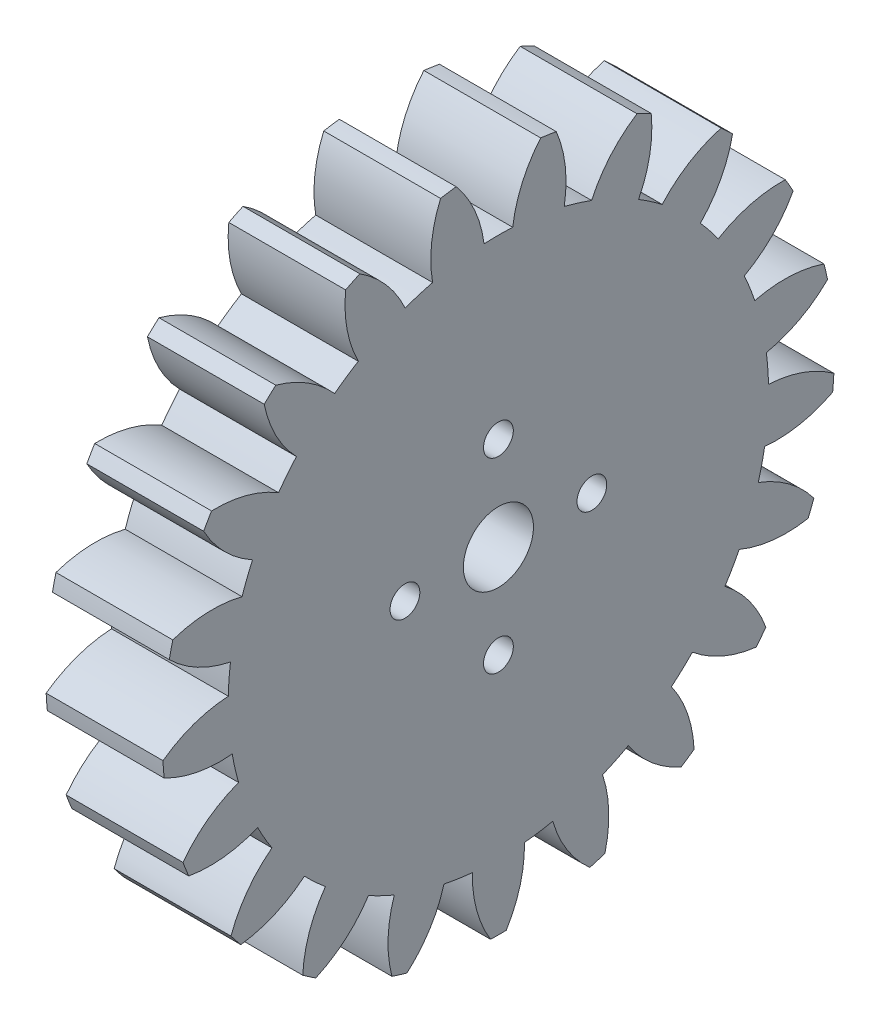
SolidWorks part; units mm, degrees
ref_plane "Plane1" through (0, 0, 0) normal (0, 0, 1) x (1, 0, 0)
ref_plane "Plane2" through (0, 0, 0) normal (0, 1, 0) x (1, 0, 0)
ref_plane "Plane3" through (0, 0, 0) normal (1, 0, 0) x (0, 0, -1)
sketch "HoldingSke" plane through (0, 0, 0) normal (0, 1, 0) x (1, 0, 0)
  line L0 (0, 0) -> (0.3734, -0.1433)
  line L1 (-15, 0) -> (100, 0) construction
  line L2 (0, 0) -> (-2.1039, 2.3779)
  line L3 (0, 0) -> (-11.863, 4.5341)
  line L4 (0, 0) -> (8.0624, 3.0949)
  line L5 (0, 0) -> (-9.3695, -3.4946)
  line L6 (0, 0) -> (-12.4344, -8.3896)
  line L7 (-2.1039, 2.3779) -> (1.1249, 17.0263)
  line L8 (-76.2, 54.61) -> (-75.2, 54.61)
  line L9 (-71.009, 38.7566) -> (-53.1078, 45.2721)
  line L10 (-76.2, 71.12) -> (104.1128, 71.12)
  line L11 (0, 0) -> (-15, 0)
  line L12 (-76.2, 101.6) -> (-76.113, 101.6)
  line L13 (24.9733, 27.94) -> (52.9518, 28.4284)
  line L14 (24.9733, 27.94) -> (24.9743, 27.94)
  line L15 (24.9733, 27.94) -> (100.4006, 29.5858)
  line L16 (-63.627, -2.5) -> (-12.827, -2.5)
  circle A0 centre (0, 0) radius 3
  circle A1 centre (0, 0) radius 12
  circle A2 centre (0, 0) radius 12
  circle A3 centre (0, 0) radius 3
  dimension "MHD" = 24
  dimension "Hub_dia" = 24
  dimension "Bore" = 6
  dimension "MBD" = 6
  dimension "Num_teeth" = 21
  dimension "Pitch" = 0.4
  dimension "Overall_len" = 10
  dimension "Show_teeth" = 21
  dimension "Thickness" = 15
  dimension "OAL" = 15.0001
  dimension "T_dim" = 1
  dimension "Ap" = 20
  dimension "H" = 19.05
  dimension "Pitch_radius" = 180.3128
  dimension "Width" = 15
  dimension "Backlash" = 0.087
  dimension "Addendum_fac" = 1
  dimension "Dedendum_fac" = 1.25
  dimension "Clearance_fac" = 0.25
  dimension "Dedendum_add" = 0.001
  dimension "Module" = 2.5
sketch "BasProSke" plane through (0, 0, 0) normal (0, 1, 0) x (1, 0, 0)
  line L0 (-10, 0) -> (60, 0) construction
  line L1 (0, 0) -> (0, 28.75)
  line L2 (0, 0) -> (15, 0)
  line L3 (15, 0) -> (15, 28.75)
  line L4 (15, 28.75) -> (0, 28.75)
  dimension "Thickness" = 15
  dimension "Diameter" = 57.5
revolve "Base-Revolve" add sketch "BasProSke" angle 360 about L0
sketch "TooCutSke" plane through (0, 0, 0) normal (1, 0, 0) x (0, 0, -1)
  line L1 (0, 0) -> (0, 107) construction
  line L2 (0, 0) -> (-2.1138, 26.1648) construction
  line L3 (0, 0) -> (-7.8061, 51.7901) construction
  line L4 (-2.1138, 26.1648) -> (-3.9031, 25.8951) construction
  arc A0 (1.226, 23.0915) -> (-1.226, 23.0915) centre (0, 0) ccw
  arc A1 (3.6363, 28.5447) -> (-3.6363, 28.5447) centre (0, 0) ccw
  circle A2 centre (0, 0) radius 26.25 construction
  circle A3 centre (0, 0) radius 24.6669 construction
  arc A4 (-1.226, 23.0915) -> (-3.6363, 28.5447) centre (-11.6397, 21.748) ccw
  arc A5 (3.6363, 28.5447) -> (1.226, 23.0915) centre (11.6397, 21.748) ccw
  dimension "Root_dia" = 46.248
  dimension "Overcut_dia" = 57.5508
  dimension "Pitch_dia" = 52.5
  dimension "Base_dia" = 49.3339
  dimension "Flank_rad" = 10.5
  dimension "Half_ang" = 8.571
  dimension "Half_CT" = 1.8094
extrude "ToothCut" cut sketch "TooCutSke" along normal through all
fillet "Breaks" [suppressed] radius 0.05
fillet "RootFillets" [suppressed] radius 0.626
pattern_circular "TeethCuts" count 21 every 17.143 about axis through (-10, 0, 0) along (1, 0, 0) of "ToothCut", "RootFillets", "Breaks"
sketch "HubNeaOneSke" plane through (0, 0, 0) normal (-1, 0, 0) x (0, 0, 1)
  circle A0 centre (0, 0) radius 12
  dimension "Diameter" = 24
extrude "HubNearOne" add sketch "HubNeaOneSke" along normal blind 35.0001
sketch "HubNeaBotSke" plane through (0, 0, 0) normal (-1, 0, 0) x (0, 0, 1)
  circle A0 centre (0, 0) radius 12
  dimension "Diameter" = 24
extrude "HubNearBoth" [suppressed] add sketch "HubNeaBotSke" along normal blind 17.5
ref_plane "FarPln" through (15, 0, 0) normal (1, 0, 0) x (0, 0, -1)
sketch "HubFarSke" plane through (15, 0, 0) normal (1, 0, 0) x (0, 0, -1)
  circle A0 centre (0, 0) radius 12
  dimension "Diameter" = 24
extrude "HubFar" [suppressed] add sketch "HubFarSke" along normal blind 17.5
sketch "BorSke" plane through (0, 0, 0) normal (1, 0, 0) x (0, 0, -1)
  circle A0 centre (0, 0) radius 3
  dimension "Diameter" = 6
extrude "Bore" cut sketch "BorSke" along normal mid plane 30.0001
sketch "KeySke" plane through (0, 0, 0) normal (1, 0, 0) x (0, 0, -1)
  line L0 (-1, 0) -> (-1, 4)
  line L1 (-1, 4) -> (1, 4)
  line L2 (1, 4) -> (1, 0)
  line L3 (0, 0) -> (0, 34) construction
  line L4 (-1, 0) -> (1, 0)
  dimension "Offset" = 4
  dimension "Width" = 2
extrude "Keyway" [suppressed] cut sketch "KeySke" along normal mid plane 30.0001
pattern_circular "Keyway2" [suppressed] count 2 every 90 about axis through (-10, 0, 0) along (1, 0, 0)
sketch "草圖1" plane through (0, 0, 0) normal (0, 1, 0) x (1, 0, 0)
  line L1 (-35.0001, -11.863) -> (-35.0001, -15.4488)
  line L2 (-35.0001, 12) -> (0, 12)
  line L3 (-35.0001, 12) -> (-35.0001, -11.863)
  line L5 (0, 12) -> (0, -11.863)
  line L6 (-35.0001, -15.4488) -> (0, -15.4488)
  line L7 (0, -15.4488) -> (0, -11.863)
extrude "除料-伸長1" cut sketch "草圖1" against normal through all both and the other way through all
sketch "草圖2" plane through (0, 0, 0) normal (-1, 0, 0) x (0, 0, 1)
  line L0 (0, 0) -> (0, 11.4291) construction
  line L1 (0, 0) -> (11.4291, 0) construction
  line L2 (0, 0) -> (0, -11.4291) construction
  line L3 (0, 0) -> (-11.4291, 0) construction
  circle A0 centre (0, 8) radius 1.275
  circle A1 centre (8, 0) radius 1.275
  circle A2 centre (0, -8) radius 1.275
  circle A3 centre (-8, 0) radius 1.275
  point P17 (0, 0)
  dimension "D1" = 8
  dimension "D2" = 2.55
  dimension "D3" = 4
extrude "除料-伸長2" cut sketch "草圖2" against normal through all
sketch "草圖3" plane through (0, 0, 0) normal (-1, 0, 0) x (0, 0, 1)
  arc A84 (15.6336, -24.1278) -> (16.7484, -23.3678) centre (0, 0) ccw
  arc A85 (16.7484, -23.3678) -> (14.8075, -17.7612) centre (6.2599, -23.8594) ccw
  arc A86 (14.8075, -17.7612) -> (16.6049, -16.0933) centre (0, 0) ccw
  arc A87 (16.6049, -16.0933) -> (22.0509, -18.4478) centre (23.3249, -8.0254) ccw
  arc A88 (22.0509, -18.4478) -> (22.8921, -17.393) centre (0, 0) ccw
  arc A89 (22.8921, -17.393) -> (19.3848, -12.6075) centre (13.0144, -20.9543) ccw
  arc A90 (19.3848, -12.6075) -> (20.6108, -10.484) centre (0, 0) ccw
  arc A91 (20.6108, -10.484) -> (26.5088, -11.1286) centre (24.6542, -0.7937) ccw
  arc A92 (26.5088, -11.1286) -> (27.0017, -9.8727) centre (0, 0) ccw
  arc A93 (27.0017, -9.8727) -> (22.2397, -6.3336) centre (18.6126, -16.1873) ccw
  arc A94 (22.2397, -6.3336) -> (22.7853, -3.9431) centre (0, 0) ccw
  arc A95 (22.7853, -3.9431) -> (28.6113, -2.8206) centre (23.7928, 6.5085) ccw
  arc A96 (28.6113, -2.8206) -> (28.7121, -1.4752) centre (0, 0) ccw
  arc A97 (28.7121, -1.4752) -> (23.1185, 0.503) centre (22.557, -9.9819) ccw
  arc A98 (23.1185, 0.503) -> (22.9353, 2.9482) centre (0, 0) ccw
  arc A99 (22.9353, 2.9482) -> (28.1716, 5.7381) centre (20.8173, 13.2324) ccw
  arc A100 (28.1716, 5.7381) -> (27.8714, 7.0534) centre (0, 0) ccw
  arc A101 (27.8714, 7.0534) -> (21.9432, 7.295) centre (24.4971, -2.8897) ccw
  arc A102 (21.9432, 7.295) -> (21.0473, 9.5775) centre (0, 0) ccw
  arc A103 (21.0473, 9.5775) -> (25.2287, 13.7868) centre (15.9922, 18.7805) ccw
  arc A104 (25.2287, 13.7868) -> (24.5541, 14.9552) centre (0, 0) ccw
  arc A105 (24.5541, 14.9552) -> (18.8181, 13.4388) centre (24.2605, 4.4593) ccw
  arc A106 (18.8181, 13.4388) -> (17.2892, 15.3558) centre (0, 0) ccw
  arc A107 (17.2892, 15.3558) -> (20.0441, 20.6106) centre (9.746, 22.6599) ccw
  arc A108 (20.0441, 20.6106) -> (19.0551, 21.5283) centre (0, 0) ccw
  arc A109 (19.0551, 21.5283) -> (14.0209, 18.3884) centre (21.8683, 11.4121) ccw
  arc A110 (14.0209, 18.3884) -> (11.9949, 19.7697) centre (0, 0) ccw
  arc A111 (11.9949, 19.7697) -> (13.0785, 25.603) centre (2.6339, 24.5259) ccw
  arc A112 (13.0785, 25.603) -> (11.863, 26.1884) centre (0, 0) ccw
  arc A113 (11.863, 26.1884) -> (7.9779, 21.7042) centre (17.5329, 17.3509) ccw
  arc A114 (7.9779, 21.7042) -> (5.6348, 22.427) centre (0, 0) ccw
  arc A115 (5.6348, 22.427) -> (4.9508, 28.3205) centre (-4.7123, 24.2126) ccw
  arc A116 (4.9508, 28.3205) -> (3.6167, 28.5216) centre (0, 0) ccw
  arc A117 (3.6167, 28.5216) -> (1.226, 23.0915) centre (11.6397, 21.748) ccw
  arc A118 (1.226, 23.0915) -> (-1.226, 23.0915) centre (0, 0) ccw
  arc A119 (-1.226, 23.0915) -> (-3.6167, 28.5216) centre (-11.6397, 21.748) ccw
  arc A120 (-3.6167, 28.5216) -> (-4.9508, 28.3205) centre (0, 0) ccw
  arc A121 (-4.9508, 28.3205) -> (-5.6348, 22.427) centre (4.7123, 24.2126) ccw
  arc A122 (-5.6348, 22.427) -> (-7.9779, 21.7042) centre (0, 0) ccw
  arc A123 (-7.9779, 21.7042) -> (-11.863, 26.1884) centre (-17.5329, 17.3509) ccw
  arc A124 (-11.863, 26.1884) -> (-13.0785, 25.603) centre (0, 0) ccw
  arc A125 (-13.0785, 25.603) -> (-11.9949, 19.7697) centre (-2.6339, 24.5259) ccw
  arc A126 (-11.9949, 19.7697) -> (-14.0209, 18.3884) centre (0, 0) ccw
  arc A127 (-14.0209, 18.3884) -> (-19.0551, 21.5283) centre (-21.8683, 11.4121) ccw
  arc A128 (-19.0551, 21.5283) -> (-20.0441, 20.6106) centre (0, 0) ccw
  arc A129 (-20.0441, 20.6106) -> (-17.2892, 15.3558) centre (-9.746, 22.6599) ccw
  arc A130 (-17.2892, 15.3558) -> (-18.8181, 13.4388) centre (0, 0) ccw
  arc A131 (-18.8181, 13.4388) -> (-24.5541, 14.9552) centre (-24.2605, 4.4593) ccw
  arc A132 (-24.5541, 14.9552) -> (-25.2287, 13.7868) centre (0, 0) ccw
  arc A133 (-25.2287, 13.7868) -> (-21.0473, 9.5775) centre (-15.9922, 18.7805) ccw
  arc A134 (-21.0473, 9.5775) -> (-21.9432, 7.295) centre (0, 0) ccw
  arc A135 (-21.9432, 7.295) -> (-27.8714, 7.0534) centre (-24.4971, -2.8897) ccw
  arc A136 (-27.8714, 7.0534) -> (-28.1716, 5.7381) centre (0, 0) ccw
  arc A137 (-28.1716, 5.7381) -> (-22.9353, 2.9482) centre (-20.8173, 13.2324) ccw
  arc A138 (-22.9353, 2.9482) -> (-23.1185, 0.503) centre (0, 0) ccw
  arc A139 (-23.1185, 0.503) -> (-28.7121, -1.4752) centre (-22.557, -9.9819) ccw
  arc A140 (-28.7121, -1.4752) -> (-28.6113, -2.8206) centre (0, 0) ccw
  arc A141 (-28.6113, -2.8206) -> (-22.7853, -3.9431) centre (-23.7928, 6.5085) ccw
  arc A142 (-22.7853, -3.9431) -> (-22.2397, -6.3336) centre (0, 0) ccw
  arc A143 (-22.2397, -6.3336) -> (-27.0017, -9.8727) centre (-18.6126, -16.1873) ccw
  arc A144 (-27.0017, -9.8727) -> (-26.5088, -11.1286) centre (0, 0) ccw
  arc A145 (-26.5088, -11.1286) -> (-20.6108, -10.484) centre (-24.6542, -0.7937) ccw
  arc A146 (-20.6108, -10.484) -> (-19.3848, -12.6075) centre (0, 0) ccw
  arc A147 (-19.3848, -12.6075) -> (-22.8921, -17.393) centre (-13.0144, -20.9543) ccw
  arc A148 (-22.8921, -17.393) -> (-22.0509, -18.4478) centre (0, 0) ccw
  arc A149 (-22.0509, -18.4478) -> (-16.6049, -16.0933) centre (-23.3249, -8.0254) ccw
  arc A150 (-16.6049, -16.0933) -> (-14.8075, -17.7612) centre (0, 0) ccw
  arc A151 (-14.8075, -17.7612) -> (-16.7484, -23.3678) centre (-6.2599, -23.8594) ccw
  arc A152 (-16.7484, -23.3678) -> (-15.6336, -24.1278) centre (0, 0) ccw
  arc A153 (-15.6336, -24.1278) -> (-11.1236, -20.2728) centre (-19.9231, -14.544) ccw
  arc A154 (-11.1236, -20.2728) -> (-8.9144, -21.3367) centre (0, 0) ccw
  arc A155 (-8.9144, -21.3367) -> (-9.1165, -27.2663) centre (1.0509, -24.6445) ccw
  arc A156 (-9.1165, -27.2663) -> (-7.8273, -27.664) centre (0, 0) ccw
  arc A157 (-7.8273, -27.664) -> (-4.6539, -22.6508) centre (-14.7511, -19.7703) ccw
  arc A158 (-4.6539, -22.6508) -> (-2.2293, -23.0163) centre (0, 0) ccw
  arc A159 (-2.2293, -23.0163) -> (-0.6746, -28.7421) centre (8.2683, -23.2399) ccw
  arc A160 (-0.6746, -28.7421) -> (0.6746, -28.7421) centre (0, 0) ccw
  arc A161 (0.6746, -28.7421) -> (2.2293, -23.0163) centre (-8.2683, -23.2399) ccw
  arc A162 (2.2293, -23.0163) -> (4.6539, -22.6508) centre (0, 0) ccw
  arc A163 (4.6539, -22.6508) -> (7.8273, -27.664) centre (14.7511, -19.7703) ccw
  arc A164 (7.8273, -27.664) -> (9.1165, -27.2663) centre (0, 0) ccw
  arc A165 (9.1165, -27.2663) -> (8.9144, -21.3367) centre (-1.0509, -24.6445) ccw
  arc A166 (8.9144, -21.3367) -> (11.1236, -20.2728) centre (0, 0) ccw
  arc A167 (11.1236, -20.2728) -> (15.6336, -24.1278) centre (19.9231, -14.544) ccw
  arc A168 (15.6336, -24.1278) -> (16.7484, -23.3678) centre (0, 0) ccw
  arc A169 (16.7484, -23.3678) -> (14.8075, -17.7612) centre (6.2599, -23.8594) ccw
  arc A170 (14.8075, -17.7612) -> (16.6049, -16.0933) centre (0, 0) ccw
  arc A171 (16.6049, -16.0933) -> (22.0509, -18.4478) centre (23.3249, -8.0254) ccw
  arc A172 (22.0509, -18.4478) -> (22.8921, -17.393) centre (0, 0) ccw
  arc A173 (22.8921, -17.393) -> (19.3848, -12.6075) centre (13.0144, -20.9543) ccw
  arc A174 (19.3848, -12.6075) -> (20.6108, -10.484) centre (0, 0) ccw
  arc A175 (20.6108, -10.484) -> (26.5088, -11.1286) centre (24.6542, -0.7937) ccw
  arc A176 (26.5088, -11.1286) -> (27.0017, -9.8727) centre (0, 0) ccw
  arc A177 (27.0017, -9.8727) -> (22.2397, -6.3336) centre (18.6126, -16.1873) ccw
  arc A178 (22.2397, -6.3336) -> (22.7853, -3.9431) centre (0, 0) ccw
  arc A179 (22.7853, -3.9431) -> (28.6113, -2.8206) centre (23.7928, 6.5085) ccw
  arc A180 (28.6113, -2.8206) -> (28.7121, -1.4752) centre (0, 0) ccw
  arc A181 (28.7121, -1.4752) -> (23.1185, 0.503) centre (22.557, -9.9819) ccw
  arc A182 (23.1185, 0.503) -> (22.9353, 2.9482) centre (0, 0) ccw
  arc A183 (22.9353, 2.9482) -> (28.1716, 5.7381) centre (20.8173, 13.2324) ccw
  arc A184 (28.1716, 5.7381) -> (27.8714, 7.0534) centre (0, 0) ccw
  arc A185 (27.8714, 7.0534) -> (21.9432, 7.295) centre (24.4971, -2.8897) ccw
  arc A186 (21.9432, 7.295) -> (21.0473, 9.5775) centre (0, 0) ccw
  arc A187 (21.0473, 9.5775) -> (25.2287, 13.7868) centre (15.9922, 18.7805) ccw
  arc A188 (25.2287, 13.7868) -> (24.5541, 14.9552) centre (0, 0) ccw
  arc A189 (24.5541, 14.9552) -> (18.8181, 13.4388) centre (24.2605, 4.4593) ccw
  arc A190 (18.8181, 13.4388) -> (17.2892, 15.3558) centre (0, 0) ccw
  arc A191 (17.2892, 15.3558) -> (20.0441, 20.6106) centre (9.746, 22.6599) ccw
  arc A192 (20.0441, 20.6106) -> (19.0551, 21.5283) centre (0, 0) ccw
  arc A193 (19.0551, 21.5283) -> (14.0209, 18.3884) centre (21.8683, 11.4121) ccw
  arc A194 (14.0209, 18.3884) -> (11.9949, 19.7697) centre (0, 0) ccw
  arc A195 (11.9949, 19.7697) -> (13.0785, 25.603) centre (2.6339, 24.5259) ccw
  arc A196 (13.0785, 25.603) -> (11.863, 26.1884) centre (0, 0) ccw
  arc A197 (11.863, 26.1884) -> (7.9779, 21.7042) centre (17.5329, 17.3509) ccw
  arc A198 (7.9779, 21.7042) -> (5.6348, 22.427) centre (0, 0) ccw
  arc A199 (5.6348, 22.427) -> (4.9508, 28.3205) centre (-4.7123, 24.2126) ccw
  arc A200 (4.9508, 28.3205) -> (3.6167, 28.5216) centre (0, 0) ccw
  arc A201 (3.6167, 28.5216) -> (1.226, 23.0915) centre (11.6397, 21.748) ccw
  arc A202 (1.226, 23.0915) -> (-1.226, 23.0915) centre (0, 0) ccw
  arc A203 (-1.226, 23.0915) -> (-3.6167, 28.5216) centre (-11.6397, 21.748) ccw
  arc A204 (-3.6167, 28.5216) -> (-4.9508, 28.3205) centre (0, 0) ccw
  arc A205 (-4.9508, 28.3205) -> (-5.6348, 22.427) centre (4.7123, 24.2126) ccw
  arc A206 (-5.6348, 22.427) -> (-7.9779, 21.7042) centre (0, 0) ccw
  arc A207 (-7.9779, 21.7042) -> (-11.863, 26.1884) centre (-17.5329, 17.3509) ccw
  arc A208 (-11.863, 26.1884) -> (-13.0785, 25.603) centre (0, 0) ccw
  arc A209 (-13.0785, 25.603) -> (-11.9949, 19.7697) centre (-2.6339, 24.5259) ccw
  arc A210 (-11.9949, 19.7697) -> (-14.0209, 18.3884) centre (0, 0) ccw
  arc A211 (-14.0209, 18.3884) -> (-19.0551, 21.5283) centre (-21.8683, 11.4121) ccw
  arc A212 (-19.0551, 21.5283) -> (-20.0441, 20.6106) centre (0, 0) ccw
  arc A213 (-20.0441, 20.6106) -> (-17.2892, 15.3558) centre (-9.746, 22.6599) ccw
  arc A214 (-17.2892, 15.3558) -> (-18.8181, 13.4388) centre (0, 0) ccw
  arc A215 (-18.8181, 13.4388) -> (-24.5541, 14.9552) centre (-24.2605, 4.4593) ccw
  arc A216 (-24.5541, 14.9552) -> (-25.2287, 13.7868) centre (0, 0) ccw
  arc A217 (-25.2287, 13.7868) -> (-21.0473, 9.5775) centre (-15.9922, 18.7805) ccw
  arc A218 (-21.0473, 9.5775) -> (-21.9432, 7.295) centre (0, 0) ccw
  arc A219 (-21.9432, 7.295) -> (-27.8714, 7.0534) centre (-24.4971, -2.8897) ccw
  arc A220 (-27.8714, 7.0534) -> (-28.1716, 5.7381) centre (0, 0) ccw
  arc A221 (-28.1716, 5.7381) -> (-22.9353, 2.9482) centre (-20.8173, 13.2324) ccw
  arc A222 (-22.9353, 2.9482) -> (-23.1185, 0.503) centre (0, 0) ccw
  arc A223 (-23.1185, 0.503) -> (-28.7121, -1.4752) centre (-22.557, -9.9819) ccw
  arc A224 (-28.7121, -1.4752) -> (-28.6113, -2.8206) centre (0, 0) ccw
  arc A225 (-28.6113, -2.8206) -> (-22.7853, -3.9431) centre (-23.7928, 6.5085) ccw
  arc A226 (-22.7853, -3.9431) -> (-22.2397, -6.3336) centre (0, 0) ccw
  arc A227 (-22.2397, -6.3336) -> (-27.0017, -9.8727) centre (-18.6126, -16.1873) ccw
  arc A228 (-27.0017, -9.8727) -> (-26.5088, -11.1286) centre (0, 0) ccw
  arc A229 (-26.5088, -11.1286) -> (-20.6108, -10.484) centre (-24.6542, -0.7937) ccw
  arc A230 (-20.6108, -10.484) -> (-19.3848, -12.6075) centre (0, 0) ccw
  arc A231 (-19.3848, -12.6075) -> (-22.8921, -17.393) centre (-13.0144, -20.9543) ccw
  arc A232 (-22.8921, -17.393) -> (-22.0509, -18.4478) centre (0, 0) ccw
  arc A233 (-22.0509, -18.4478) -> (-16.6049, -16.0933) centre (-23.3249, -8.0254) ccw
  arc A234 (-16.6049, -16.0933) -> (-14.8075, -17.7612) centre (0, 0) ccw
  arc A235 (-14.8075, -17.7612) -> (-16.7484, -23.3678) centre (-6.2599, -23.8594) ccw
  arc A236 (-16.7484, -23.3678) -> (-15.6336, -24.1278) centre (0, 0) ccw
  arc A237 (-15.6336, -24.1278) -> (-11.1236, -20.2728) centre (-19.9231, -14.544) ccw
  arc A238 (-11.1236, -20.2728) -> (-8.9144, -21.3367) centre (0, 0) ccw
  arc A239 (-8.9144, -21.3367) -> (-9.1165, -27.2663) centre (1.0509, -24.6445) ccw
  arc A240 (-9.1165, -27.2663) -> (-7.8273, -27.664) centre (0, 0) ccw
  arc A241 (-7.8273, -27.664) -> (-4.6539, -22.6508) centre (-14.7511, -19.7703) ccw
  arc A242 (-4.6539, -22.6508) -> (-2.2293, -23.0163) centre (0, 0) ccw
  arc A243 (-2.2293, -23.0163) -> (-0.6746, -28.7421) centre (8.2683, -23.2399) ccw
  arc A244 (-0.6746, -28.7421) -> (0.6746, -28.7421) centre (0, 0) ccw
  arc A245 (0.6746, -28.7421) -> (2.2293, -23.0163) centre (-8.2683, -23.2399) ccw
  arc A246 (2.2293, -23.0163) -> (4.6539, -22.6508) centre (0, 0) ccw
  arc A247 (4.6539, -22.6508) -> (7.8273, -27.664) centre (14.7511, -19.7703) ccw
  arc A248 (7.8273, -27.664) -> (9.1165, -27.2663) centre (0, 0) ccw
  arc A249 (9.1165, -27.2663) -> (8.9144, -21.3367) centre (-1.0509, -24.6445) ccw
  arc A250 (8.9144, -21.3367) -> (11.1236, -20.2728) centre (0, 0) ccw
  arc A251 (11.1236, -20.2728) -> (15.6336, -24.1278) centre (19.9231, -14.544) ccw
  dimension "D1" = 0
extrude "除料-伸長3" cut sketch "草圖3" against normal blind 5
equation "' \"Module@HoldingSke\" = 6.35"
equation "' \"Num_teeth@HoldingSke\" = 12"
equation "' \"Ap@HoldingSke\" =  20"
equation "' \"Ap@HoldingSke\" = 20"
equation "' \"Width@HoldingSke\" = 0.5 * 25.4"
equation "' \"Hub_dia@HoldingSke\"= 1 * 25.4"
equation "' \"Hub_dia@HoldingSke\" = 1 * 25.4"
equation "' \"Overall_len@HoldingSke\" = 1.0 * 25.4"
equation "' \"Bore@HoldingSke\" = 0.75 * 25.4"
equation "' \"T_dim@HoldingSke\" = 0.1 * 25.4"
equation "' \"Width@KeySke\" = 0.25 * 25.4"
equation "' \"Show_teeth@HoldingSke\" = 13"
equation "' \"Backlash@HoldingSke\" = 0.009 * 25.4"
equation "' \"Addendum_fac@HoldingSke\" = 1.0"
equation "' \"Dedendum_fac@HoldingSke\" = 1.25"
equation "' \"Dedendum_add@HoldingSke\" = 0.00005 * 25.4"
equation "' \"Clearance_fac@HoldingSke\" = 0.25"
equation "\"Pitch@HoldingSke\" = 1 / \"Module@HoldingSke\""
equation "\"Overcut_dia@TooCutSke\" = (\"Num_teeth@HoldingSke\" + 2 * \"Addendum_fac@HoldingSke\") / \"Pitch@HoldingSke\" + 0.002 * 25.4"
equation "\"Pitch_dia@TooCutSke\" = \"Num_teeth@HoldingSke\" / \"Pitch@HoldingSke\""
equation "\"Base_dia@TooCutSke\" = \"Num_teeth@HoldingSke\" / \"Pitch@HoldingSke\" * cos((\"Ap@HoldingSke\"  * 3.14159265 / 180))"
equation "\"Root_dia@TooCutSke\" = (\"Num_teeth@HoldingSke\" + 2) / \"Pitch@HoldingSke\" - 2 * (\"Addendum_fac@HoldingSke\" + \"Dedendum_fac@HoldingSke\") / \"Pitch@HoldingSke\" - \"Dedendum_add@HoldingSke\" * 2"
equation "\"Half_ang@TooCutSke\" = 180 / \"Num_teeth@HoldingSke\""
equation "\"Half_CT@TooCutSke\" = \"Num_teeth@HoldingSke\" / \"Pitch@HoldingSke\" * sin((3.14159265 / 2 / \"Num_teeth@HoldingSke\")) / 2 - 7 * \"Backlash@HoldingSke\" / 4"
equation "\"Flank_rad@TooCutSke\" = \"Num_teeth@HoldingSke\" / \"Pitch@HoldingSke\" / 5"
equation "\"Radius@RootFillets\" = \"Clearance_fac@HoldingSke\" / \"Pitch@HoldingSke\" + \"Dedendum_add@HoldingSke\""
equation "\"Break_rad@Breaks\" = 0.02 / \"Pitch@HoldingSke\""
equation "\"Thickness@HoldingSke\" = \"Width@HoldingSke\""
equation "\"OAL@HoldingSke\" = \"Thickness@HoldingSke\""
equation "\"MHD@HoldingSke\" = (\"Num_teeth@HoldingSke\" + 2) / \"Pitch@HoldingSke\" - 2 * (\"Addendum_fac@HoldingSke\" + \"Dedendum_fac@HoldingSke\")  / \"Pitch@HoldingSke\" - \"Dedendum_add@HoldingSke\" * 2"
equation "\"MBD@HoldingSke\" = (\"Num_teeth@HoldingSke\" + 2) / \"Pitch@HoldingSke\" - 2 * (\"Addendum_fac@HoldingSke\" + \"Dedendum_fac@HoldingSke\")  / \"Pitch@HoldingSke\" - \"Dedendum_add@HoldingSke\" * 2 - 0.002 * 25.4"
equation "\"MHD@HoldingSke\" = ((sgn( \"MHD@HoldingSke\" - \"Hub_dia@HoldingSke\" )-1)*( \"MHD@HoldingSke\" - \"Hub_dia@HoldingSke\" ))/-2+ \"Hub_dia@HoldingSke\""
equation "\"MBD@HoldingSke\" = ((sgn( \"MBD@HoldingSke\" - \"Bore@HoldingSke\" )-1)*( \"MBD@HoldingSke\" - \"Bore@HoldingSke\" ))/-2+ \"Bore@HoldingSke\""
equation "\"OAL@HoldingSke\" = ((sgn( \"OAL@HoldingSke\" - \"Overall_len@HoldingSke\" )+1)*( \"OAL@HoldingSke\" - \"Overall_len@HoldingSke\" ))/2 + \"Overall_len@HoldingSke\" + 0.000002 * 25.4"
equation "\"Num_teeth@TeethCuts\" = int( \"Show_teeth@HoldingSke\" ) + 1"
equation "\"Num_teeth@TeethCuts\" = ((sgn( \"Num_teeth@TeethCuts\" - \"Num_teeth@HoldingSke\" )-1)*( \"Num_teeth@TeethCuts\" - \"Num_teeth@HoldingSke\" ))/-2+ \"Num_teeth@HoldingSke\""
equation "\"Num_teeth@TeethCuts\" = ((sgn( \"Num_teeth@TeethCuts\" - 2.0)+1)*( \"Num_teeth@TeethCuts\" - 2.0))/2 +2.0"
equation "\"Angle@TeethCuts\" = 360.0 / \"Num_teeth@HoldingSke\""
equation "\"Diameter@BasProSke\" = (\"Num_teeth@HoldingSke\" + 2 * \"Addendum_fac@HoldingSke\") / \"Pitch@HoldingSke\""
equation "\"Thickness@BasProSke\"  = \"Thickness@HoldingSke\""
equation "' \"Fillet_rad@BasProSke\" =  \"Thickness@HoldingSke\" * 0.05"
equation "' \"Fillet_rad@BasProSke\" = \"Thickness@HoldingSke\" * 0.05"
equation "\"MHD@HoldingSke\" = ((sgn( \"MHD@HoldingSke\" - \"Root_dia@TooCutSke\" )-1)*( \"MHD@HoldingSke\" - \"Root_dia@TooCutSke\" ))/-2+ \"Root_dia@TooCutSke\""
equation "\"Diameter@HubNeaOneSke\" = \"MHD@HoldingSke\""
equation "\"Length@HubNearOne\" = \"OAL@HoldingSke\" - \"Thickness@BasProSke\""
equation "\"Diameter@HubNeaBotSke\" = \"MHD@HoldingSke\""
equation "\"Length@HubNearBoth\" = ( \"OAL@HoldingSke\" - \"Thickness@BasProSke\" ) / 2.0"
equation "\"Thickness@FarPln\" = \"Thickness@BasProSke\""
equation "\"Diameter@HubFarSke\" = \"MHD@HoldingSke\""
equation "\"Length@HubFar\" = ( \"OAL@HoldingSke\" - \"Thickness@BasProSke\" ) / 2.0"
equation "\"Diameter@BorSke\" = \"MBD@HoldingSke\""
equation "\"D1@Bore\" = \"OAL@HoldingSke\" * 2.0"
equation "\"D1@Keyway\" = \"OAL@HoldingSke\" * 2.0"
equation "\"Offset@KeySke\" = \"T_dim@HoldingSke\" + \"MBD@HoldingSke\" / 2.0"
